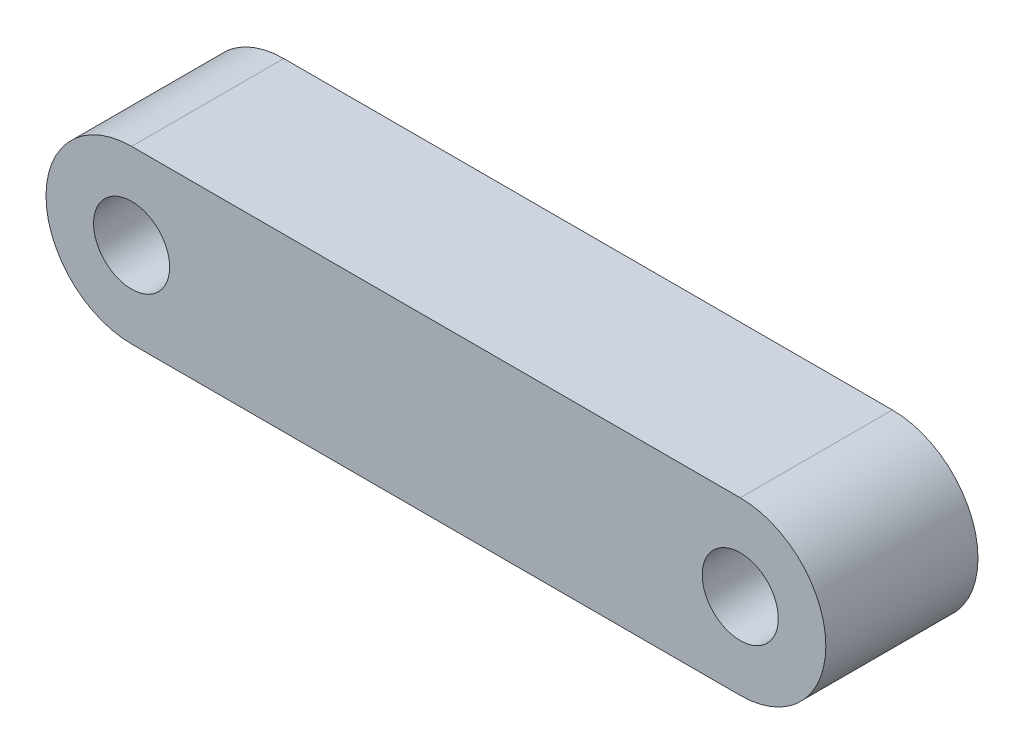
SolidWorks part; units mm, degrees
ref_plane "Front" through (0, 0, 0) normal (0, 0, 1) x (1, 0, 0)
ref_plane "Top" through (0, 0, 0) normal (0, 1, 0) x (1, 0, 0)
ref_plane "Right" through (0, 0, 0) normal (1, 0, 0) x (0, 0, -1)
sketch "Esquisse1" plane through (0, 0, 0) normal (0, 0, 1) x (1, 0, 0)
  line L1 (0, 0) -> (32, 0)
  line L2 (0, 0) -> (0, 9)
  line L3 (0, 9) -> (32, 9)
  line L4 (32, 0) -> (32, 9)
  dimension "D1" = 9
  dimension "D2" = 32
extrude "Boss.-Extru.1" add sketch "Esquisse1" along normal blind 8
sketch "Esquisse2" plane through (0, 0, 8) normal (0, 0, 1) x (1, 0, 0)
  line L0 (16, 0) -> (16, 9) construction
  line L1 (0, 0) -> (32, 0) construction
  line L2 (32, 9) -> (0, 9) construction
  line L3 (0, 9) -> (0, 0) construction
  line L4 (0, 0) -> (0, 9)
  line L5 (32, 0) -> (32, 9)
  arc A0 (0, 9) -> (0, 0) centre (0, 4.5) ccw
  arc A1 (32, 9) -> (32, 0) centre (32, 4.5) cw
extrude "Boss.-Extru.2" add sketch "Esquisse2" against normal up to vertex (8 mm away) up to point (32, 9, 0)
sketch "Esquisse3" plane through (0, 0, 8) normal (0, 0, 1) x (1, 0, 0)
  line L0 (0, 0) -> (0, 9) construction
  line L1 (32, 9) -> (32, 0) construction
  arc A0 (32, 0) -> (32, 9) centre (32, 4.5) ccw construction
  circle A1 centre (32, 4.5) radius 2
  circle A2 centre (0, 4.5) radius 2
  dimension "D1" = 4
extrude "Enlèv. mat.-Extru.1" cut sketch "Esquisse3" against normal through all
